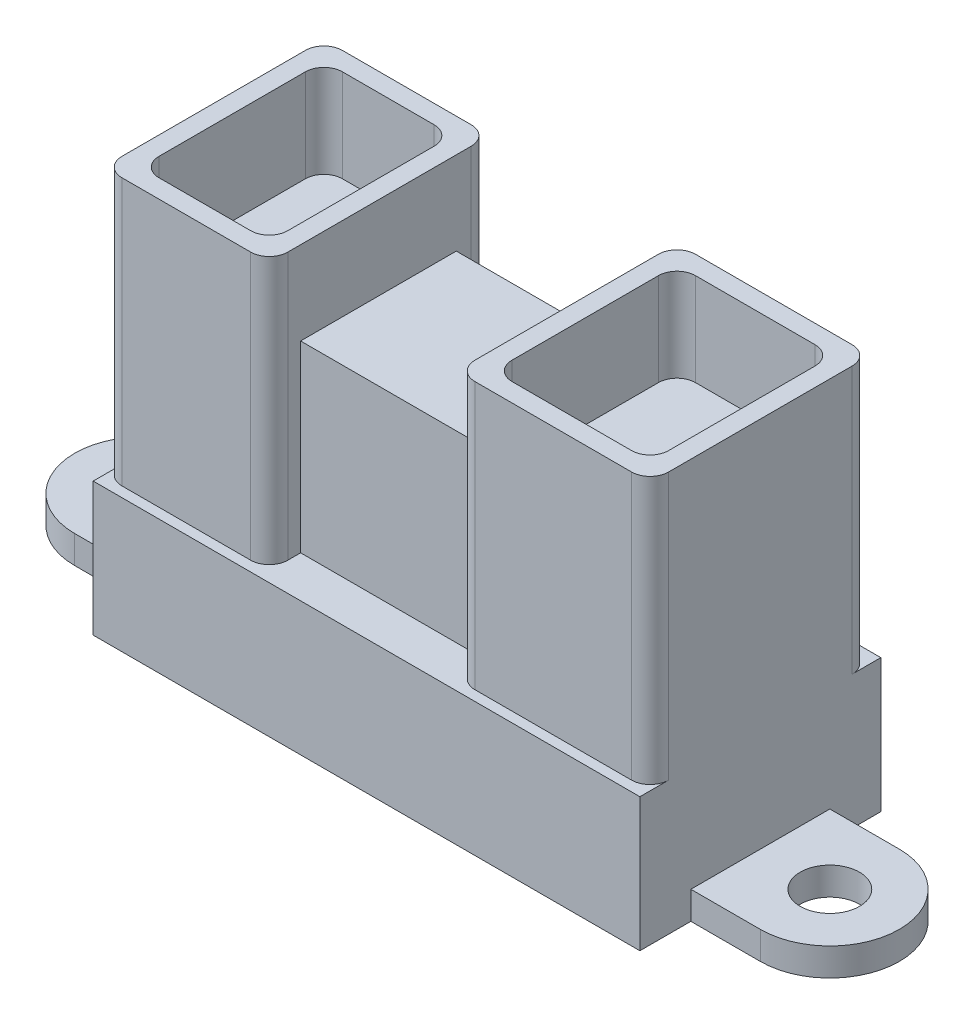
SolidWorks part; units mm, degrees
ref_plane "Front Plane" through (0, 0, 0) normal (0, 0, 1) x (1, 0, 0)
ref_plane "Top Plane" through (0, 0, 0) normal (0, 1, 0) x (1, 0, 0)
ref_plane "Right Plane" through (0, 0, 0) normal (1, 0, 0) x (0, 0, -1)
sketch "Sketch3" plane through (0, 0, 0) normal (0, 1, 0) x (1, 0, 0)
  line L1 (-14.75, 6.5) -> (14.75, 6.5)
  line L2 (-14.75, 6.5) -> (-14.75, -6.5)
  line L3 (-14.75, -6.5) -> (14.75, -6.5)
  line L4 (14.75, 6.5) -> (14.75, -6.5)
  line L5 (-14.75, 6.5) -> (14.75, -6.5) construction
  line L6 (-14.75, -6.5) -> (14.75, 6.5) construction
  point P0 (0, 0)
  dimension "D1" = 29.5
  dimension "D2" = 13
extrude "Boss-Extrude2" add sketch "Sketch3" along normal blind 7.2
sketch "Sketch5" plane through (0, 0, 0) normal (0, 1, 0) x (1, 0, 0)
  line L0 (-18.5, 3.75) -> (-14.75, 3.75)
  line L1 (-14.75, 6.5) -> (-14.75, -6.5) construction
  line L2 (-14.75, 3.75) -> (-14.75, -3.75)
  line L3 (-14.75, -3.75) -> (-18.5, -3.75)
  line L4 (-18.5, 0) -> (0, 0) construction
  arc A0 (-18.5, 3.75) -> (-18.5, -3.75) centre (-18.5, 0) ccw
  circle A1 centre (-18.5, 0) radius 1.6
  dimension "D3" = 3.2
  dimension "D1" = 7.5
  dimension "D2" = 3.75
  dimension "D4" = 18.5
extrude "Boss-Extrude3" add sketch "Sketch5" along normal blind 1.5
mirror "Mirror1" about plane through (0, 0, 0) normal (1, 0, 0) of "Boss-Extrude3"
sketch "Sketch9" plane through (0, 7.2, 0) normal (0, 1, 0) x (1, 0, 0)
  line L0 (-14.75, 6.5) -> (-14.75, -6.5) construction
  line L1 (-5.8, 5.95) -> (-14.75, 5.95)
  line L2 (-5.8, 5.95) -> (-5.8, -5.95)
  line L3 (-5.8, -5.95) -> (-14.75, -5.95)
  line L4 (-14.75, 5.95) -> (-14.75, -5.95)
  line L5 (-5.8, 5.95) -> (-14.75, -5.95) construction
  line L6 (-5.8, -5.95) -> (-14.75, 5.95) construction
  line L7 (14.75, -6.5) -> (14.75, 6.5) construction
  line L8 (4.3, 5.95) -> (14.75, 5.95)
  line L9 (4.3, 5.95) -> (4.3, -5.95)
  line L10 (4.3, -5.95) -> (14.75, -5.95)
  line L11 (14.75, 5.95) -> (14.75, -5.95)
  line L12 (4.3, 5.95) -> (14.75, -5.95) construction
  line L13 (4.3, -5.95) -> (14.75, 5.95) construction
  line L15 (-10.275, 0) -> (0, 0) construction
  line L16 (0, 0) -> (9.525, 0) construction
  point P0 (-10.275, 0)
  point P7 (9.525, 0)
  dimension "D1" = 11.9
  dimension "D2" = 8.95
  dimension "D3" = 11.9
  dimension "D4" = 10.45
  dimension "D5" = 19.8
extrude "Boss-Extrude4" add sketch "Sketch9" along normal blind 14.4
sketch "Sketch10" plane through (0, 7.2, 0) normal (0, 1, 0) x (1, 0, 0)
  line L0 (-5.8, -5.95) -> (-5.8, 5.95) construction
  line L1 (-5.8, 4.1425) -> (4.3, 4.1425)
  line L2 (-5.8, 4.1425) -> (-5.8, -4.2575)
  line L3 (-5.8, -4.2575) -> (4.3, -4.2575)
  line L4 (4.3, 4.1425) -> (4.3, -4.2575)
  line L5 (4.3, 5.95) -> (4.3, -5.95) construction
  dimension "D1" = 8.4
extrude "Boss-Extrude5" add sketch "Sketch10" along normal blind 9.9
sketch "Sketch11" plane through (0, 21.6, 0) normal (0, 1, 0) x (1, 0, 0)
  line L0 (-5.8, 5.95) -> (-14.75, 5.95) construction
  line L1 (-13.75, 4.95) -> (-6.8, 4.95)
  line L2 (-13.75, 4.95) -> (-13.75, -4.95)
  line L3 (-13.75, -4.95) -> (-6.8, -4.95)
  line L4 (-6.8, 4.95) -> (-6.8, -4.95)
  line L5 (-5.8, -5.95) -> (-5.8, 5.95) construction
  line L6 (-14.75, -5.95) -> (-5.8, -5.95) construction
  line L7 (-14.75, -3.75) -> (-14.75, 3.75) construction
  line L8 (4.3, -4.2575) -> (4.3, 4.1425) construction
  line L9 (5.3, 4.95) -> (13.75, 4.95)
  line L10 (5.3, 4.95) -> (5.3, -4.95)
  line L11 (5.3, -4.95) -> (13.75, -4.95)
  line L12 (13.75, 4.95) -> (13.75, -4.95)
  line L13 (4.3, -5.95) -> (14.75, -5.95) construction
  line L14 (14.75, -3.75) -> (14.75, 3.75) construction
  line L15 (14.75, 5.95) -> (4.3, 5.95) construction
  dimension "D1" = 1
  dimension "D2" = 1
  dimension "D3" = 1
  dimension "D4" = 1
  dimension "D5" = 1
  dimension "D6" = 1
  dimension "D7" = 1
  dimension "D8" = 1
extrude "Cut-Extrude2" cut sketch "Sketch11" against normal blind 5
fillet "Fillet2" radius 1 16 edges at (-14.75, 14.4, 5.95) (-5.8, 14.4, 5.95) (4.3, 14.4, 5.95) (14.75, 14.4, 5.95) (14.75, 14.4, -5.95) (4.3, 14.4, -5.95) (-5.8, 14.4, -5.95) (-14.75, 14.4, -5.95) (5.3, 19.1, -4.95) (13.75, 19.1, -4.95) (13.75, 19.1, 4.95) (5.3, 19.1, 4.95) (-6.8, 19.1, 4.95) (-13.75, 19.1, 4.95) (-6.8, 19.1, -4.95) (-13.75, 19.1, -4.95)
